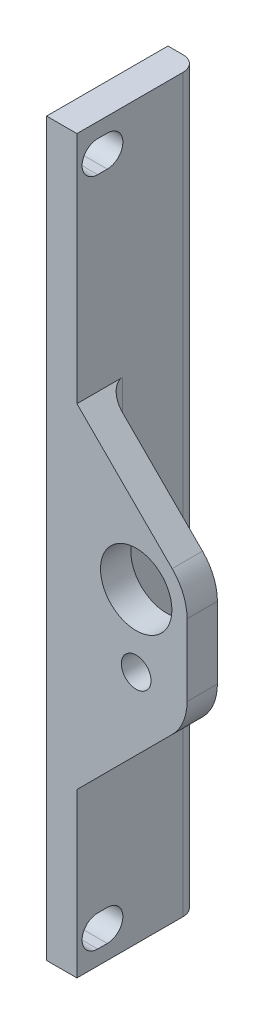
SolidWorks part; units mm, degrees
ref_plane "Front Plane" through (0, 0, 0) normal (0, 0, 1) x (1, 0, 0)
ref_plane "Top Plane" through (0, 0, 0) normal (0, 1, 0) x (1, 0, 0)
ref_plane "Right Plane" through (0, 0, 0) normal (1, 0, 0) x (0, 0, -1)
sketch "Sketch1" plane through (0, 0, 0) normal (1, 0, 0) x (0, 0, -1)
  line L0 (0, 0) -> (50000, 0) construction
  line L1 (-4.3472, -76.5247) -> (4.3472, -76.5247)
  line L2 (-4.3472, -76.5247) -> (-4.3472, 76.5247)
  line L3 (-4.3472, 76.5247) -> (4.3472, 76.5247)
  line L5 (-4.3472, -76.5247) -> (4.3472, 76.5247) construction
  line L6 (-4.3472, 76.5247) -> (4.3472, -76.5247) construction
  line L7 (0, 70.1747) -> (2, 70.1747) construction
  line L8 (4.3472, 76.5247) -> (21.0528, 76.5247)
  line L10 (4.3472, -76.5247) -> (21.0528, -76.5247)
  line L11 (21.0528, 76.5247) -> (21.0528, -76.5247)
  line L12 (0, 73.4386) -> (2, 73.4386)
  line L13 (0, 66.9108) -> (2, 66.9108)
  line L14 (0, -66.9108) -> (2, -66.9108)
  line L15 (0, -73.4386) -> (2, -73.4386)
  arc A0 (0, 73.4386) -> (0, 66.9108) centre (0, 70.1747) ccw
  arc A2 (2, 66.9108) -> (2, 73.4386) centre (2, 70.1747) ccw
  arc A3 (2, -66.9108) -> (2, -73.4386) centre (2, -70.1747) cw
  arc A4 (0, -73.4386) -> (0, -66.9108) centre (0, -70.1747) cw
  point P0 (0, 0)
  dimension "D1" = 6.5278
  dimension "D2" = 140.3495
  dimension "D7" = 2
  dimension "D3" = 8.6944
  dimension "D4" = 6.35
  dimension "D5" = 25.4
  dimension "D6" = 4.3472
extrude "Boss-Extrude1" add sketch "Sketch1" along normal blind 6.35
sketch "Sketch2" plane through (0, 0, 4.3472) normal (0, 0, 1) x (1, 0, 0)
  line L0 (6.35, 27.5677) -> (26.2812, 7.6365)
  line L1 (6.35, 76.5247) -> (6.35, -76.5247) construction
  line L2 (29.4005, 0.1058) -> (29.4005, -14.8942)
  line L3 (26.2812, -22.4249) -> (6.35, -42.3561)
  line L4 (6.35, -42.3561) -> (6.35, 27.5677)
  line L5 (6.35, 76.5247) -> (0, 76.5247) construction
  line L6 (0, 76.5247) -> (0, -76.5247) construction
  circle A0 centre (18.7505, 0.1058) radius 7.475
  circle A1 centre (18.7505, -14.8942) radius 3.1
  arc A2 (26.2812, 7.6365) -> (29.4005, 0.1058) centre (18.7505, 0.1058) cw
  arc A3 (29.4005, -14.8942) -> (26.2812, -22.4249) centre (18.7505, -14.8942) cw
  dimension "D2" = 18.7505
  dimension "D3" = 15
  dimension "D4" = 14.95
  dimension "D5" = 6.2
  dimension "D6" = 3.175
  dimension "D1" = 76.4189
  dimension "D8" = 45
  dimension "D9" = 45
extrude "Boss-Extrude2" add sketch "Sketch2" against normal blind 6.35
fillet "Fillet1" radius 3.175 2 edges at (6.35, 0, -21.0528) (6.35, -7.3942, -2.0028)
